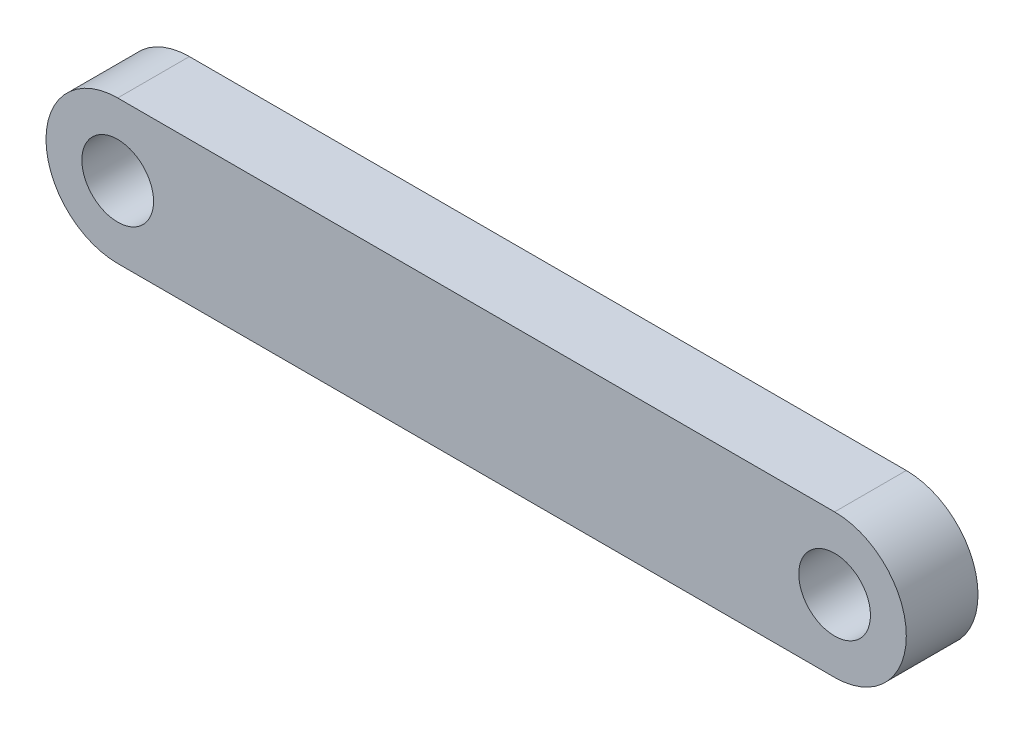
SolidWorks part; units mm, degrees
ref_plane "Front Plane" through (0, 0, 0) normal (0, 0, 1) x (1, 0, 0)
ref_plane "Top Plane" through (0, 0, 0) normal (0, 1, 0) x (1, 0, 0)
ref_plane "Right Plane" through (0, 0, 0) normal (1, 0, 0) x (0, 0, -1)
sketch "Sketch1" plane through (0, 0, 0) normal (0, 0, 1) x (1, 0, 0)
  line L0 (-50, 0) -> (50, 0) construction
  line L1 (-50, 10) -> (50, 10)
  line L2 (-50, -10) -> (50, -10)
  arc A1 (-50, 10) -> (-50, -10) centre (-50, 0) ccw
  arc A2 (50, -10) -> (50, 10) centre (50, 0) ccw
  circle A3 centre (-50, 0) radius 5
  circle A4 centre (50, 0) radius 5
  point P3 (0, 0)
  dimension "D1" = 100
  dimension "D3" = 10
  dimension "D4" = 10
  dimension "D2" = 20
extrude "Boss-Extrude3" add sketch "Sketch1" along normal blind 10
sketch "Sketch2" plane through (0, 0, 0) normal (0, 0, 1) x (1, 0, 0)
  point P0 (-50, 0)
  point P1 (50, 0)
